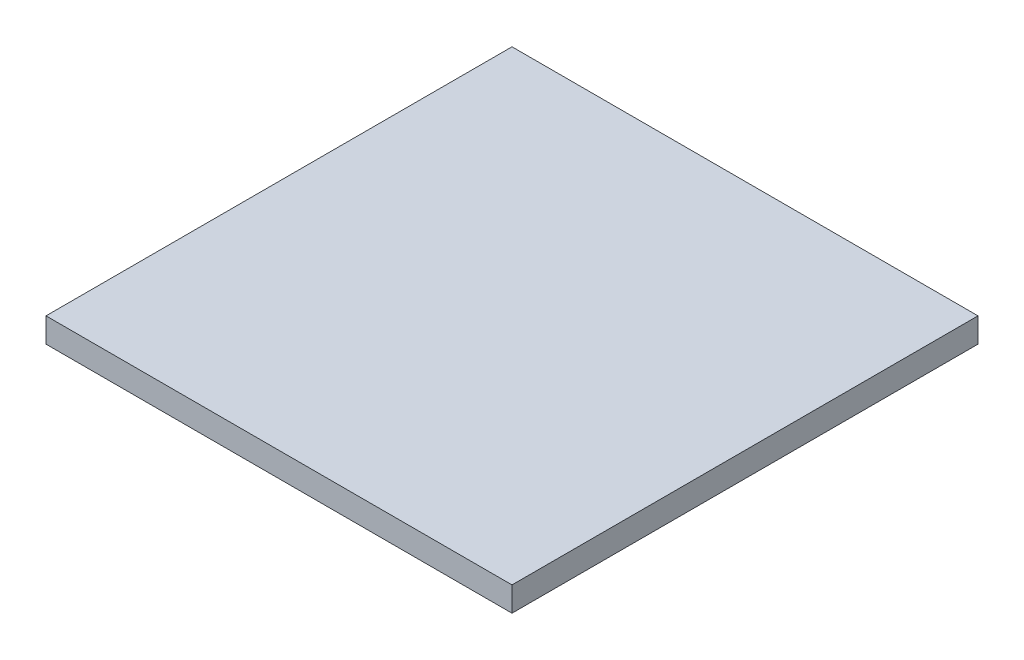
SolidWorks part; units mm, degrees
ref_plane "Alzado" through (0, 0, 0) normal (0, 0, 1) x (1, 0, 0)
ref_plane "Planta" through (0, 0, 0) normal (0, 1, 0) x (1, 0, 0)
ref_plane "Vista lateral" through (0, 0, 0) normal (1, 0, 0) x (0, 0, -1)
sketch "Croquis2" plane through (0, 0, 0) normal (0, 1, 0) x (1, 0, 0)
  line L1 (0, 0) -> (95, 0)
  line L2 (0, 0) -> (0, 95)
  line L3 (0, 95) -> (95, 95)
  line L4 (95, 0) -> (95, 95)
  dimension "D1" = 95
  dimension "D2" = 95
extrude "Saliente-Extruir1" add sketch "Croquis2" along normal blind 5
